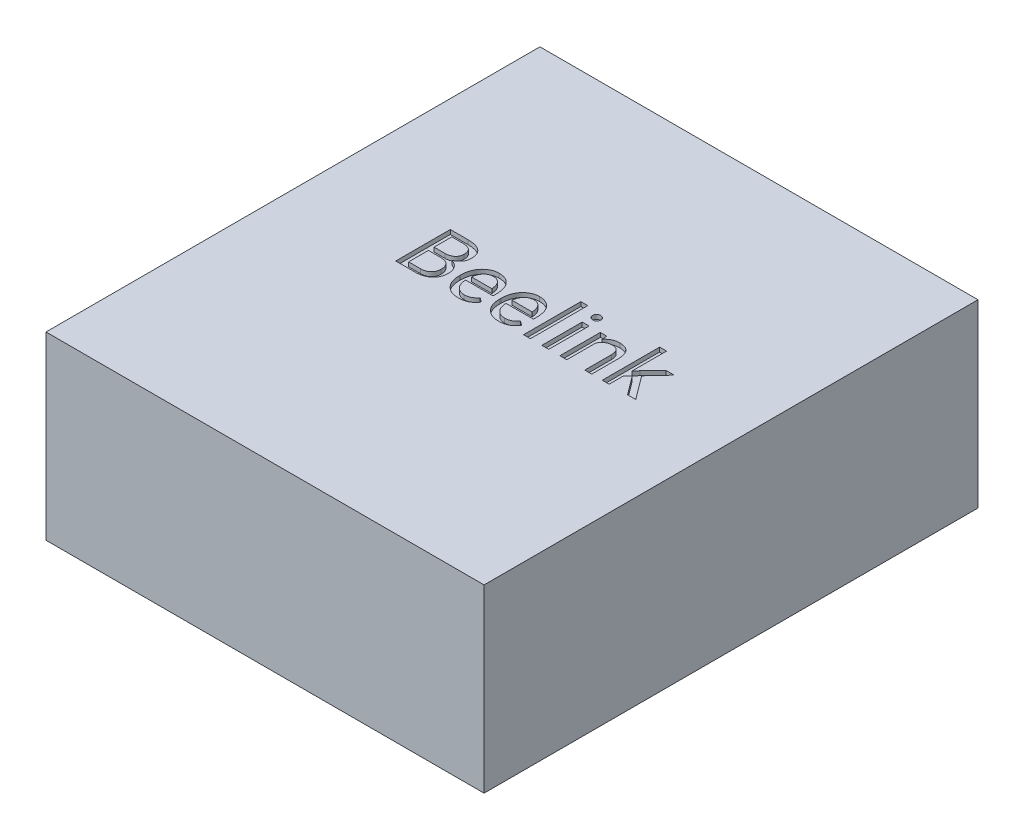
SolidWorks part; units mm, degrees
ref_plane "Front Plane" through (0, 0, 0) normal (0, 0, 1) x (1, 0, 0)
ref_plane "Top Plane" through (0, 0, 0) normal (0, 1, 0) x (1, 0, 0)
ref_plane "Right Plane" through (0, 0, 0) normal (1, 0, 0) x (0, 0, -1)
sketch "Sketch1" plane through (0, 0, 0) normal (0, 1, 0) x (1, 0, 0)
  line L1 (0, 0) -> (102, 0)
  line L2 (0, 0) -> (0, 115)
  line L3 (0, 115) -> (102, 115)
  line L4 (102, 0) -> (102, 115)
  dimension "D1" = 115
  dimension "D2" = 102
extrude "Boss-Extrude1" add sketch "Sketch1" along normal mid plane 42
sketch "Sketch2" plane through (0, 21, 0) normal (0, 1, 0) x (1, 0, 0)
  text T0 "Beelink" font "Roboto" height 12.7
extrude "Cut-Extrude1" cut sketch "Sketch2" against normal blind 1
equation "\"D1@Sketch1\"=115mm"
equation "\"D2@Sketch1\"=102mm"
equation "\"D1@Boss-Extrude1\"=42mm"
